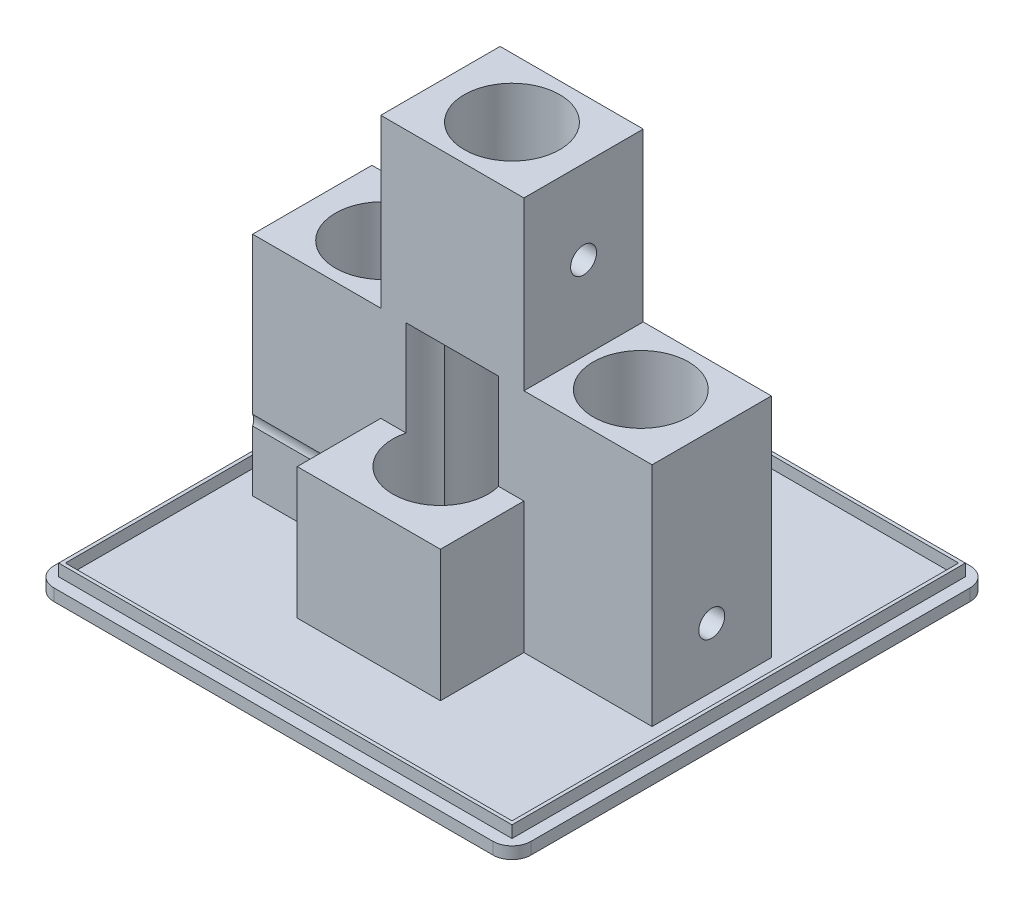
SolidWorks part; units mm, degrees
ref_plane "Front Plane" through (0, 0, 0) normal (0, 0, 1) x (1, 0, 0)
ref_plane "Top Plane" through (0, 0, 0) normal (0, 1, 0) x (1, 0, 0)
ref_plane "Right Plane" through (0, 0, 0) normal (1, 0, 0) x (0, 0, -1)
sketch "Sketch1" plane through (0, 0, 0) normal (0, 0, 1) x (1, 0, 0)
  line L1 (-9.525, -9.525) -> (9.525, -9.525)
  line L2 (-9.525, -9.525) -> (-9.525, 9.525)
  line L3 (-9.525, 9.525) -> (9.525, 9.525)
  line L4 (9.525, -9.525) -> (9.525, 9.525)
  line L5 (-9.525, -9.525) -> (9.525, 9.525) construction
  line L6 (-9.525, 9.525) -> (9.525, -9.525) construction
  point P0 (0, 0)
  dimension "D1" = 19.05
  dimension "D2" = 19.05
extrude "Boss-Extrude1" add sketch "Sketch1" along normal blind 38.1
sketch "Sketch6" plane through (0, 9.525, 0) normal (0, 1, 0) x (1, 0, 0)
  line L0 (0, 0) -> (0, -38.1) construction
  line L1 (9.525, -11.1125) -> (-9.525, -11.1125)
  line L2 (9.525, -11.1125) -> (9.525, -26.9875)
  line L3 (9.525, -26.9875) -> (-9.525, -26.9875)
  line L4 (-9.525, -11.1125) -> (-9.525, -26.9875)
  line L5 (9.525, -11.1125) -> (-9.525, -26.9875) construction
  line L6 (9.525, -26.9875) -> (-9.525, -11.1125) construction
  line L7 (9.525, 0) -> (-9.525, 0) construction
  line L8 (9.525, -38.1) -> (-9.525, -38.1) construction
  line L9 (9.525, -19.05) -> (-9.525, -19.05) construction
  line L10 (9.525, -38.1) -> (9.525, 0) construction
  line L11 (-9.525, -38.1) -> (-9.525, 0) construction
  line L13 (5.6066, -11.1125) -> (9.525, -11.1125) construction
  point P0 (0, -19.05)
  dimension "D1" = 15.875
extrude "Boss-Extrude3" add sketch "Sketch6" along normal blind 34.925
sketch "Sketch2" plane through (0, -9.525, 0) normal (0, -1, 0) x (-1, 0, 0)
  line L0 (0, -38.1) -> (0, 0) construction
  line L1 (9.525, -38.1) -> (-9.525, -38.1) construction
  line L2 (9.525, 0) -> (-9.525, 0) construction
  line L3 (0, -19.05) -> (-9.525, -19.05) construction
  line L4 (-9.525, -38.1) -> (-9.525, 0) construction
  circle A0 centre (0, -28.575) radius 6.35
  circle A2 centre (0, -9.525) radius 6.35
  dimension "D3" = 12.7
  dimension "D5" = 12.7
  dimension "D1" = 9.525
  dimension "D2" = 9.525
extrude "Cut-Extrude1" cut sketch "Sketch2" against normal blind 31.75
sketch "Sketch8" plane through (0, 44.45, 0) normal (0, 1, 0) x (1, 0, 0)
  line L0 (0, -26.9875) -> (0, -11.1125) construction
  line L1 (9.525, -11.1125) -> (-9.525, -11.1125) construction
  line L3 (-9.525, -26.9875) -> (9.525, -26.9875) construction
  line L7 (0, -11.1125) -> (-9.525, -19.05) construction
  line L8 (-9.525, -11.1125) -> (-9.525, -26.9875) construction
  line L9 (-9.525, -19.05) -> (9.525, -19.05) construction
  line L10 (9.525, -26.9875) -> (9.525, -11.1125) construction
  circle A0 centre (0, -19.05) radius 6.35
  point P4 (0, -11.1125)
  dimension "D1" = 12.7
  dimension "D2" = 7.9375
extrude "Cut-Extrude4" cut sketch "Sketch8" against normal through all
sketch "Sketch10" plane through (0, -9.525, 0) normal (0, -1, 0) x (-1, 0, 0)
  line L0 (-9.525, -38.1) -> (-9.525, 0) construction
  line L1 (-9.525, -26.9875) -> (-26.575, -26.9875)
  line L2 (-9.525, -26.9875) -> (-9.525, -11.1125)
  line L3 (-9.525, -11.1125) -> (-26.575, -11.1125)
  line L4 (-26.575, -26.9875) -> (-26.575, -11.1125)
  line L5 (0, -19.05) -> (-26.575, -19.05) construction
  dimension "D1" = 15.875
  dimension "D2" = 17.05
extrude "Boss-Extrude4" add sketch "Sketch10" against normal up to surface (31.75 mm away) up to face at (0, 22.225, 12.3762)
sketch "Sketch11" plane through (0, -9.525, 0) normal (0, -1, 0) x (-1, 0, 0)
  line L0 (-18.05, -26.9875) -> (-18.05, -11.1125) construction
  line L1 (-26.575, -26.9875) -> (-9.525, -26.9875) construction
  line L2 (-9.525, -11.1125) -> (-26.575, -11.1125) construction
  line L3 (-18.05, -11.1125) -> (-26.575, -19.05) construction
  line L4 (-26.575, -11.1125) -> (-26.575, -26.9875) construction
  line L5 (-26.575, -19.05) -> (0, -19.05) construction
  circle A0 centre (-17.145, -19.05) radius 6.35
  dimension "D1" = 12.7
  dimension "D2" = 17.145
extrude "Cut-Extrude6" cut sketch "Sketch11" against normal up to surface (31.75 mm away) up to face at (0, 22.225, 12.3762)
sketch "Sketch12" plane through (26.575, 0, 0) normal (1, 0, 0) x (0, 0, -1)
  line L0 (-19.05, -9.525) -> (-19.05, 22.225) construction
  line L1 (-11.1125, -9.525) -> (-26.9875, -9.525) construction
  line L2 (-26.9875, 22.225) -> (-11.1125, 22.225) construction
  circle A0 centre (-19.05, 0) radius 1.7272
  dimension "D1" = 3.4544
  dimension "D2" = 9.525
extrude "Cut-Extrude7" cut sketch "Sketch12" against normal up to next
mirror "Mirror1" about plane through (0, 0, 0) normal (1, 0, 0) of "Cut-Extrude7", "Cut-Extrude6", "Boss-Extrude4"
sketch "Sketch13" plane through (0, -9.525, 0) normal (0, -1, 0) x (-1, 0, 0)
  line L78 (0, -38.1) -> (0, 0) construction
  line L79 (31.75, 12.7) -> (-31.75, 12.7)
  line L80 (31.75, 12.7) -> (31.75, -50.8)
  line L81 (31.75, -50.8) -> (-31.75, -50.8)
  line L82 (-31.75, 12.7) -> (-31.75, -50.8)
  line L83 (31.75, 12.7) -> (-31.75, -50.8) construction
  line L84 (31.75, -50.8) -> (-31.75, 12.7) construction
  line L90 (9.525, -26.9875) -> (26.575, -26.9875)
  line L91 (26.575, -26.9875) -> (26.575, -11.1125)
  line L92 (26.575, -11.1125) -> (9.525, -11.1125)
  line L93 (9.525, -11.1125) -> (9.525, 0)
  line L94 (9.525, 0) -> (-9.525, 0)
  line L95 (-9.525, 0) -> (-9.525, -11.1125)
  line L96 (-9.525, -11.1125) -> (-26.575, -11.1125)
  line L97 (-26.575, -11.1125) -> (-26.575, -26.9875)
  line L98 (-26.575, -26.9875) -> (-9.525, -26.9875)
  line L99 (-9.525, -26.9875) -> (-9.525, -38.1)
  line L100 (-9.525, -38.1) -> (9.525, -38.1)
  line L101 (9.525, -38.1) -> (9.525, -26.9875)
  line L102 (9.525, -26.9875) -> (26.575, -26.9875)
  line L103 (26.575, -26.9875) -> (26.575, -11.1125)
  line L104 (26.575, -11.1125) -> (9.525, -11.1125)
  line L105 (9.525, -11.1125) -> (9.525, 0)
  line L106 (9.525, 0) -> (-9.525, 0)
  line L107 (-9.525, 0) -> (-9.525, -11.1125)
  line L108 (-9.525, -11.1125) -> (-26.575, -11.1125)
  line L109 (-26.575, -11.1125) -> (-26.575, -26.9875)
  line L110 (-26.575, -26.9875) -> (-9.525, -26.9875)
  line L111 (-9.525, -26.9875) -> (-9.525, -38.1)
  line L112 (-9.525, -38.1) -> (9.525, -38.1)
  line L113 (9.525, -38.1) -> (9.525, -26.9875)
  point P10 (0, -19.05)
  point P20 (0, -14.7066)
  point P21 (0, -19.05)
  dimension "D2" = 63.5
  dimension "D3" = 63.5
  dimension "D4" = 31.75
  dimension "D1" = 0
extrude "Boss-Extrude5" add sketch "Sketch13" against normal blind 1.5875
sketch "Sketch15" plane through (9.525, 0, 0) normal (1, 0, 0) x (0, 0, -1)
  line L0 (-19.05, 22.225) -> (-19.05, 44.45) construction
  line L1 (-11.1125, 22.225) -> (-26.9875, 22.225) construction
  line L2 (-26.9875, 44.45) -> (-11.1125, 44.45) construction
  circle A0 centre (-19.05, 33.3375) radius 1.7272
  dimension "D1" = 3.4544
extrude "Cut-Extrude9" cut sketch "Sketch15" against normal up to next
sketch "Sketch16" plane through (0, -7.9375, 0) normal (0, 1, 0) x (1, 0, 0)
  line L4 (-29.7125, -48.7625) -> (29.7125, -48.7625)
  line L5 (29.7125, -48.7625) -> (29.7125, 10.6625)
  line L6 (29.7125, 10.6625) -> (-29.7125, 10.6625)
  line L7 (-29.7125, 10.6625) -> (-29.7125, -48.7625)
  line L8 (30.1625, -49.2125) -> (30.1625, 11.1125)
  line L9 (30.1625, 11.1125) -> (-30.1625, 11.1125)
  line L10 (-30.1625, 11.1125) -> (-30.1625, -49.2125)
  line L11 (-30.1625, -49.2125) -> (30.1625, -49.2125)
  line L12 (30.1625, -49.2125) -> (30.1625, 11.1125)
  line L13 (30.1625, 11.1125) -> (-30.1625, 11.1125)
  line L14 (-30.1625, 11.1125) -> (-30.1625, -49.2125)
  line L15 (-30.1625, -49.2125) -> (30.1625, -49.2125)
  dimension "D1" = 1.5875
  dimension "D2" = 0.45
extrude "Boss-Extrude6" add sketch "Sketch16" along normal blind 1.5875
fillet "Fillet1" radius 2.54 4 edges at (-31.75, -8.7312, 50.8) (-31.75, -8.7312, -12.7) (31.75, -8.7312, -12.7) (31.75, -8.7312, 50.8)
sketch "Sketch18" plane through (-9.525, 0, 0) normal (-1, 0, 0) x (0, 0, 1)
  line L0 (28.575, 9.525) -> (28.575, -7.9375) construction
  line L1 (38.1, 9.525) -> (26.9875, 9.525) construction
  line L2 (38.1, -7.9375) -> (26.9875, -7.9375) construction
  line L3 (38.1, 9.525) -> (38.1, -7.9375) construction
  line L4 (19.05, 0) -> (19.05, 44.9144) construction
  circle A0 centre (28.575, 0.7938) radius 1.7272
  circle A1 centre (9.525, 0.7938) radius 1.7272
  dimension "D2" = 3.4544
  dimension "D1" = 9.525
extrude "Cut-Extrude10" cut sketch "Sketch18" against normal up to next and the other way through all
